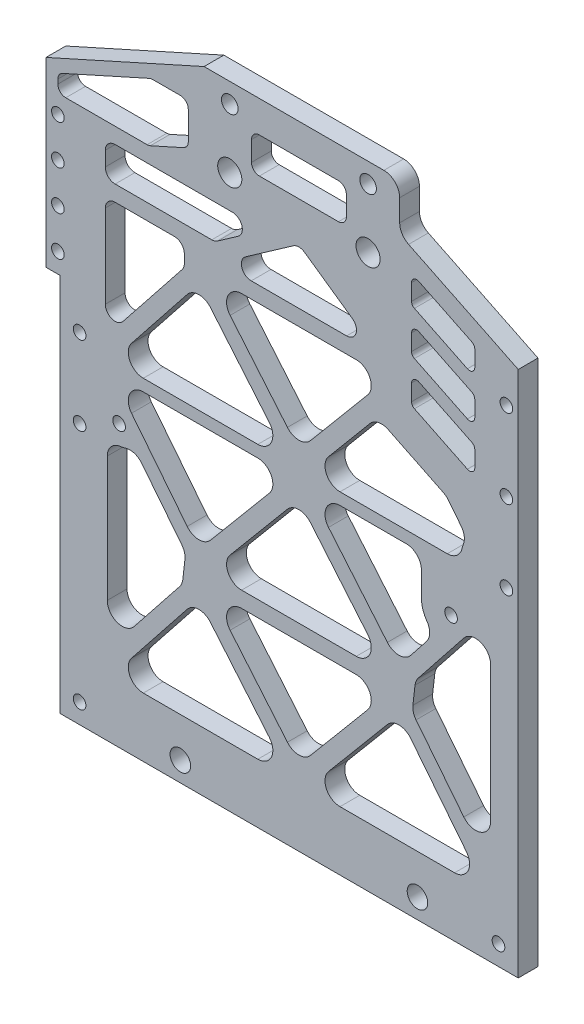
SolidWorks part; units mm, degrees
material "环氧树脂FR-4"
ref_plane "前视基准面" through (0, 0, 0) normal (0, 0, 1) x (1, 0, 0)
ref_plane "上视基准面" through (0, 0, 0) normal (0, 1, 0) x (1, 0, 0)
ref_plane "右视基准面" through (0, 0, 0) normal (1, 0, 0) x (0, 0, -1)
sketch "草图1" plane through (0, 0, 0) normal (0, 0, 1) x (1, 0, 0)
  line L1 (55.5, -80) -> (-55.5, -80)
  line L2 (55.5, -80) -> (55.5, 80)
  line L3 (55.5, 80) -> (-55.5, 80)
  line L4 (-55.5, -80) -> (-55.5, 80)
  line L5 (55.5, -80) -> (-55.5, 80) construction
  line L6 (55.5, 80) -> (-55.5, -80) construction
  point P0 (0, 0)
  dimension "D1" = 111
  dimension "D2" = 160
extrude "凸台-拉伸1" add sketch "草图1" along normal blind 5
sketch "草图2" plane through (0, 0, 5) normal (0, 0, 1) x (1, 0, 0)
  line L0 (0, 80) -> (0, -80) construction
  line L1 (55.5, 80) -> (-55.5, 80) construction
  line L2 (-55.5, -80) -> (55.5, -80) construction
  circle A0 centre (-30, -75) radius 2.6
  circle A1 centre (30, -75) radius 2.6
  dimension "D3" = 5.2
  dimension "D1" = 60
  dimension "D2" = 5
extrude "切除-拉伸1" cut sketch "草图2" against normal through all
sketch "草图6" plane through (0, 0, 5) normal (0, 0, 1) x (1, 0, 0)
  line L0 (0, 80) -> (0, -80) construction
  line L1 (55.5, 80) -> (-55.5, 80) construction
  line L2 (-55.5, -80) -> (55.5, -80) construction
  line L4 (17.5, 60) -> (-17.5, 60) construction
  line L5 (17.5, 60) -> (17.5, 75) construction
  line L6 (17.5, 75) -> (-17.5, 75) construction
  line L7 (-17.5, 60) -> (-17.5, 75) construction
  line L8 (17.5, 60) -> (-17.5, 75) construction
  line L9 (17.5, 75) -> (-17.5, 60) construction
  circle A2 centre (-17.5, 75) radius 2.1
  circle A3 centre (17.5, 75) radius 2.1
  circle A4 centre (17.5, 60) radius 3.0525
  circle A5 centre (-17.5, 60) radius 3.0525
  point P6 (0, 67.5)
  dimension "D4" = 4.2
  dimension "D5" = 6.105
  dimension "D1" = 35
  dimension "D2" = 15
  dimension "D3" = 12.5
extrude "切除-拉伸4" cut sketch "草图6" against normal through all
sketch "草图7" plane through (0, 0, 5) normal (0, 0, 1) x (1, 0, 0)
  line L0 (-17.5, 75) -> (-17.5, 60) construction
  line L2 (17.5, 75) -> (17.5, 60) construction
  line L4 (-17.5, 67.5) -> (17.5, 67.5) construction
  line L6 (10, 63) -> (-10, 63)
  line L7 (12, 65) -> (12, 70)
  line L8 (10, 72) -> (-10, 72)
  line L9 (-12, 65) -> (-12, 70)
  line L10 (12, 63) -> (-12, 72) construction
  line L11 (12, 72) -> (-12, 63) construction
  arc A0 (12, 70) -> (10, 72) centre (10, 70) ccw
  arc A1 (10, 63) -> (12, 65) centre (10, 65) ccw
  arc A2 (-10, 63) -> (-12, 65) centre (-10, 65) cw
  arc A3 (-10, 72) -> (-12, 70) centre (-10, 70) ccw
  point P10 (0, 67.5)
  dimension "D3" = 2
  dimension "D1" = 24
  dimension "D2" = 9
extrude "切除-拉伸5" cut sketch "草图7" against normal through all
sketch "草图8" plane through (0, 0, 5) normal (0, 0, 1) x (1, 0, 0)
  line L5 (25.5, 80) -> (25.5, 68)
  line L8 (55.5, 80) -> (-55.5, 80) construction
  line L9 (25.5, 68) -> (55.5, 53.368)
  line L10 (55.5, -80) -> (55.5, 80) construction
  line L11 (55.5, 53.368) -> (55.5, 80)
  line L12 (55.5, 80) -> (25.5, 80)
  dimension "D1" = 26
  dimension "D2" = 12
  dimension "D3" = 30
extrude "切除-拉伸6" cut sketch "草图8" against normal through all
fillet "圆角1" radius 4 2 edges at (25.5, 80, 2.5) (25.5, 68, 2.5)
sketch "草图10" plane through (0, 0, 0) normal (0, 0, 1) x (1, 0, 0)
  line L0 (-55.5, 80) -> (-64, 80)
  line L1 (-64, 80) -> (-64, 16)
  line L2 (-64, 16) -> (-55.5, 16)
  line L3 (-55.5, 80) -> (-55.5, -80) construction
  line L4 (-55.5, 16) -> (-55.5, 80)
  dimension "D1" = 8.5
  dimension "D2" = 64
extrude "凸台-拉伸3" add sketch "草图10" along normal up to surface (5 mm away) up to face at (12.5699, 33.4098, 5)
sketch "草图11" plane through (0, 0, 5) normal (0, 0, 1) x (1, 0, 0)
  line L0 (-61, 41) -> (-61, 21) construction
  line L1 (-64, 80) -> (-64, 16) construction
  line L2 (-64, 16) -> (-55.5, 16) construction
  line L3 (-61, 51) -> (-61, 41) construction
  circle A0 centre (-61, 21) radius 1.6
  circle A1 centre (-61, 41) radius 1.6
  circle A2 centre (-61, 31) radius 1.6
  circle A3 centre (-61, 51) radius 1.6
  dimension "D3" = 3.2
  dimension "D1" = 20
  dimension "D2" = 3
  dimension "D4" = 5
  dimension "D5" = 10
extrude "切除-拉伸7" cut sketch "草图11" against normal through all
sketch "草图12" plane through (0, 0, 5) normal (0, 0, 1) x (1, 0, 0)
  line L0 (-64, 80) -> (-64, 62)
  line L1 (-64, 80) -> (-64, 16) construction
  line L2 (-64, 62) -> (-24, 80)
  line L3 (21.5, 80) -> (-64, 80) construction
  line L4 (-24, 80) -> (-64, 80)
  dimension "D1" = 18
  dimension "D2" = 40
extrude "切除-拉伸8" cut sketch "草图12" against normal through all
sketch "草图13" plane through (0, 0, 0) normal (0, 0, 1) x (1, 0, 0)
  line L0 (-55.5, -80) -> (-60.5, -80)
  line L1 (-60.5, -80) -> (-60.5, 16)
  line L2 (-64, 16) -> (-55.5, 16) construction
  line L3 (-60.5, 16) -> (-55.5, 16)
  line L4 (-55.5, 16) -> (-55.5, -80) construction
  line L5 (-55.5, 16) -> (-55.5, -80)
  dimension "D1" = 5
extrude "凸台-拉伸4" add sketch "草图13" along normal up to surface (5 mm away) up to face at (-4.6764, 32.8435, 5)
sketch "草图19" plane through (0, 0, 5) normal (0, 0, 1) x (1, 0, 0)
  line L0 (-55.5, -75) -> (50.5, -75) construction
  line L1 (-60.5, 16) -> (-60.5, -80) construction
  line L2 (-60.5, -80) -> (55.5, -80) construction
  line L3 (-55.5, 6) -> (-55.5, -14) construction
  line L4 (-64, 16) -> (-60.5, 16) construction
  line L5 (52.5, 44) -> (52.5, 24) construction
  line L6 (55.5, -80) -> (55.5, 53.368) construction
  line L7 (52.5, 24) -> (52.5, 4) construction
  circle A0 centre (-55.5, -75) radius 1.6
  circle A1 centre (50.5, -75) radius 1.6
  circle A2 centre (-55.5, 6) radius 1.6
  circle A3 centre (-55.5, -14) radius 1.6
  circle A4 centre (52.5, 44) radius 1.6
  circle A5 centre (52.5, 24) radius 1.6
  circle A6 centre (52.5, 4) radius 1.6
  dimension "D1" = 3.2
  dimension "D2" = 5
  dimension "D11" = 20
  dimension "D3" = 5
  dimension "D4" = 20
  dimension "D5" = 5
  dimension "D6" = 10
  dimension "D7" = 5
  dimension "D8" = 20
  dimension "D9" = 3
  dimension "D10" = 44
extrude "切除-拉伸13" cut sketch "草图19" against normal through all
sketch "草图14" plane through (0, 0, 5) normal (0, 0, 1) x (1, 0, 0)
  line L0 (28.5, 60.9738) -> (44.5, 53.1701)
  line L1 (44.5, 53.1701) -> (44.5, 46.1701)
  line L2 (44.5, 46.1701) -> (28.5, 53.9738)
  line L3 (28.5, 53.9738) -> (28.5, 60.9738)
  line L4 (27.7465, 66.9043) -> (55.5, 53.368) construction
  line L5 (55.5, -80) -> (55.5, 53.368) construction
  line L6 (25.5, 76) -> (25.5, 70.4995) construction
  dimension "D1" = 5
  dimension "D2" = 11
  dimension "D3" = 3
  dimension "D4" = 7
extrude "切除-拉伸9" cut sketch "草图14" against normal through all
fillet "圆角2" radius 1.3 4 edges at (44.5, 46.1701, 2.5) (44.5, 53.1701, 2.5) (28.5, 53.9738, 2.5) (28.5, 60.9738, 2.5)
pattern_linear "阵列(线性)1" count 3 spacing 11 along (0, -1, 0) of "切除-拉伸9", "圆角2"
sketch "草图17" plane through (0, 0, 5) normal (0, 0, 1) x (1, 0, 0)
  line L0 (-61, 60.0602) -> (-37.4444, 70.6602)
  line L1 (-28, 70.6602) -> (-28, 55.6602)
  line L3 (-64, 62) -> (-24, 80) construction
  line L4 (-61, 60.0602) -> (-61, 55.6602)
  line L5 (-61, 55.6602) -> (-28, 55.6602)
  line L6 (-64, 62) -> (-64, 16) construction
  line L7 (-37.4444, 70.6602) -> (-28, 70.6602)
  dimension "D1" = 3
  dimension "D2" = 3
  dimension "D3" = 4.4
  dimension "D4" = 33
  dimension "D5" = 15
extrude "切除-拉伸11" cut sketch "草图17" against normal through all
chamfer "倒角2" distance 10 angle 24.23 1 edges at (-28, 55.6602, 2.5)
fillet "圆角3" radius 2 6 edges at (-61, 60.0602, 2.5) (-28, 70.6602, 2.5) (-37.4444, 70.6602, 2.5) (-61, 55.6602, 2.5) (-38, 55.6602, 2.5) (-28, 60.1607, 2.5)
sketch "草图21" plane through (0, 0, 5) normal (0, 0, 1) x (1, 0, 0)
  line L0 (38.5, -9) -> (-45.5, -9) construction
  line L1 (-60.5, -80) -> (55.5, -80) construction
  circle A0 centre (-45.5, -9) radius 1.6
  circle A1 centre (38.5, -9) radius 1.6
  dimension "D1" = 84
  dimension "D2" = 71
  dimension "D3" = 3.2
  dimension "D4" = 38.5
extrude "切除-拉伸14" cut sketch "草图21" against normal through all
sketch "草图20" plane through (0, 0, 0) normal (0, 0, -1) x (-1, 0, 0)
  line L6 (0, 0) -> (0, -80) construction
  line L7 (60.5, -80) -> (-55.5, -80) construction
  line L14 (22.6557, -34) -> (-22.6557, -34)
  line L22 (-22.6557, -34) -> (0, -61)
  line L23 (-2.25, -65) -> (-25.3804, -37.4343)
  line L24 (-25.3804, -37.4343) -> (-47.25, -65)
  line L25 (-47.25, -65) -> (-2.25, -65)
  line L29 (60.5, -80) -> (-55.5, -80) construction
  line L30 (0, 2.5) -> (60.5, 2.5) construction
  line L38 (47.25, -65) -> (2.25, -65)
  line L39 (25.3804, -37.4343) -> (47.25, -65)
  line L40 (2.25, -65) -> (25.3804, -37.4343)
  line L41 (22.6557, -34) -> (0, -61)
  line L43 (0, -32) -> (60.5, -32) construction
  line L44 (60.5, 16) -> (60.5, -80) construction
  line L45 (22.6557, -30) -> (-22.6557, -30)
  line L46 (-22.6557, -34) -> (0, -61)
  line L47 (-2.25, -65) -> (-25.3804, -37.4343)
  line L48 (-25.3804, -37.4343) -> (-47.25, -65)
  line L49 (-47.25, -65) -> (-2.25, -65)
  line L53 (-25.3804, -26.5657) -> (-47.25, 1)
  line L54 (47.25, -65) -> (2.25, -65)
  line L55 (25.3804, -37.4343) -> (47.25, -65)
  line L56 (2.25, -65) -> (25.3804, -37.4343)
  line L57 (22.6557, -34) -> (0, -61)
  line L58 (-47.25, 1) -> (-2.25, 1)
  line L59 (-2.25, 1) -> (-25.3804, -26.5657)
  line L60 (-22.6557, -30) -> (0, -3)
  line L61 (47.25, 1) -> (2.25, 1)
  line L62 (25.3804, -26.5657) -> (47.25, 1)
  line L63 (2.25, 1) -> (25.3804, -26.5657)
  line L64 (22.6557, -30) -> (0, -3)
  line L65 (-48.5, -60.1397) -> (-26.1749, -32)
  line L66 (-31, 1) -> (-31, -9)
  line L67 (31, 1) -> (31, -9)
  line L68 (25.3804, 31.5657) -> (47.25, 4)
  line L69 (2.25, 4) -> (25.3804, 31.5657)
  line L71 (-48.5, -3.8603) -> (-48.5, -60.1397)
  line L72 (-55.5, -80) -> (-55.5, 53.368) construction
  line L73 (48.5, -60.1397) -> (26.1749, -32)
  line L74 (48.5, -3.8603) -> (48.5, -60.1397)
  line L75 (48.5, -3.8603) -> (26.1749, -32)
  line L76 (-48.5, -3.8603) -> (-26.1749, -32)
  line L77 (47.25, 4) -> (2.25, 4)
  line L78 (22.6557, 35) -> (0, 8)
  line L79 (-22.6557, 35) -> (0, 8)
  line L80 (22.6557, 35) -> (-22.6557, 35)
  line L81 (-2.25, 4) -> (-25.3804, 31.5657)
  line L82 (-47.25, 4) -> (-2.25, 4)
  line L83 (-25.3804, 31.5657) -> (-47.25, 4)
  line L84 (-19.9047, 25.04) -> (-37.2816, 16.5647)
  line L85 (-29.2301, 31.6177) -> (-42.6301, 25.0821) construction
  line L86 (-48.5, -16.5) -> (-38.5, -16.5)
  line L87 (-38.5, -1.5) -> (-38.5, 1)
  circle A2 centre (-38.5, -9) radius 7.5
  circle A5 centre (-52.5, 4) radius 11.6321
  circle A6 centre (45.5, -9) radius 4.8443
  point P17 (-43.6454, -3.5434)
  point P31 (0, -34)
  point P59 (48.5, -32)
  point P60 (-48.5, -32)
  dimension "D7" = 15
  dimension "D3" = 3
  dimension "D1" = 15
  dimension "D2" = 4.5
  dimension "D4" = 27
  dimension "D5" = 40
  dimension "D6" = 45
  dimension "D8" = 4
  dimension "D9" = 7
  dimension "D10" = 10
  dimension "D11" = 19
  dimension "D12" = 2
extrude "切除-拉伸22" cut sketch "草图20" against normal through all
chamfer "倒角1" distance 4 angle 45 2 edges at (-26.1749, -32, 2.5) (26.1749, -32, 2.5)
fillet "圆角5" radius 3.8 39 edges at (22.6557, -34, 2.5) (-22.6557, -34, 2.5) (0, -61, 2.5) (-47.25, -65, 2.5) (-2.25, -65, 2.5) (-25.3804, -37.4343, 2.5) (2.25, 1, 2.5) (25.3804, -26.5657, 2.5) (34.3566, -15.2516, 2.5) (0, -3, 2.5) (-22.6557, -30, 2.5) (-29.5058, -36.1984, 2.5) (-28.661, -28.8664, 2.5) (-48.5, -60.1397, 2.5) (29.5058, -27.8016, 2.5) (28.661, -35.1336, 2.5) (48.5, -60.1397, 2.5) (25.3804, -37.4343, 2.5) (2.25, -65, 2.5) (47.25, -65, 2.5) (-25.3804, -26.5657, 2.5) (-2.25, 1, 2.5) (-47.25, 1, 2.5) (22.6557, -30, 2.5) (31, 1, 2.5) (22.6557, 35, 2.5) (-22.6557, 35, 2.5) (0, 8, 2.5) (2.25, 4, 2.5) (40.8679, 4, 2.5) (42.5154, 9.9677, 2.5) (-25.3804, 31.5657, 2.5) (-47.25, 4, 2.5) (-2.25, 4, 2.5) (19.9047, 25.04, 2.5) (37.2816, 16.5647, 2.5) (-48.5, -12.8035, 2.5) (-41.8739, -12.2122, 2.5) (48.5, -3.8603, 2.5)
sketch "草图23" plane through (0, 0, 0) normal (0, 0, -1) x (-1, 0, 0)
  line L0 (-22.5, 8) -> (-44.5, 8)
  line L1 (-44.5, 8) -> (-44.5, 18)
  line L2 (-44.5, 18) -> (-30.6678, 24.7464)
  line L4 (0.2882, 8) -> (-12.2588, 33.7251)
  line L5 (-12.2588, 33.7251) -> (3.8979, 41.6052)
  line L6 (3.8979, 41.6052) -> (20.2882, 8)
  line L7 (20.2882, 8) -> (0.2882, 8)
  line L8 (25.8512, 8) -> (8.3918, 43.7971)
  line L10 (45.8512, 32.8401) -> (45.8512, 8)
  line L11 (45.8512, 8) -> (25.8512, 8)
  line L12 (-27.2, 1) -> (-10.3991, 1) construction
  line L13 (-29.2301, 31.6177) -> (-42.6301, 25.0821) construction
  line L14 (-44.5, 26.2505) -> (-44.5, 30.3577) construction
  line L15 (-19.1622, 8) -> (-27.9714, 26.0615)
  line L16 (-27.9714, 26.0615) -> (-15.8539, 31.9716)
  line L17 (-15.8539, 31.9716) -> (-4.1622, 8)
  line L18 (-4.1622, 8) -> (-19.1622, 8)
  line L20 (8.3918, 43.7971) -> (14.6834, 46.8657)
  line L21 (-37.629, 8) -> (28.9212, 40.4587)
  line L22 (-30.7855, 8) -> (32.4806, 38.8569)
  line L23 (20.2882, 8) -> (45.8512, 20.4679)
  line L24 (13.4447, 8) -> (45.8512, 23.8057)
  line L25 (-30.6678, 24.7464) -> (-22.5, 8)
  line L26 (14.6834, 46.8657) -> (45.8512, 32.8401)
  line L27 (37.8359, 70.4841) -> (59.8207, 60.5909) construction
  dimension "D1" = 7
  dimension "D2" = 22
  dimension "D3" = 10
  dimension "D4" = 3
  dimension "D5" = 4
  dimension "D6" = 15
  dimension "D7" = 20
  dimension "D8" = 5
  dimension "D9" = 20
  dimension "D10" = 12
  dimension "D11" = 3
  dimension "D12" = 3
  dimension "D13" = 7
extrude "切除-拉伸23" [suppressed] cut sketch "草图23" against normal through all contours L25 L2 L1 L0 L21 | L15 L21 L17 L16 | L22 L15 L18 L17 | L7 L24 L6 L22 L4 | L4 L21 L6 L5 | L26 L20 L8 L21 | L26 L22 L8 L24 L10 | L23 L8 L11 L10
sketch "草图24" plane through (0, 0, 0) normal (0, 0, -1) x (-1, 0, 0)
  line L1 (49, 39) -> (49, 8.23)
  line L2 (49, 8.23) -> (29, 33.4391)
  line L3 (29, 33.4391) -> (29, 39)
  line L4 (-20, 39) -> (0, 53)
  line L7 (0, 53) -> (20, 39)
  line L8 (20, 39) -> (-20, 39)
  line L9 (0, 53) -> (0, 0) construction
  line L10 (14.5066, 35) -> (-14.5066, 35) construction
  line L12 (28.2748, 27.9174) -> (42.3615, 10.1618) construction
  line L14 (64, 62) -> (64, 16) construction
  line L15 (49, 39) -> (29, 39)
  line L16 (8.8891, 51.6602) -> (21.2609, 43)
  line L17 (21.2609, 43) -> (49, 43)
  line L18 (49, 43) -> (49, 51.6602)
  line L19 (49, 51.6602) -> (8.8891, 51.6602)
  line L20 (59, 55.6602) -> (38.4293, 55.6602) construction
  point P12 (0, 39)
  dimension "D1" = 4
  dimension "D2" = 14
  dimension "D3" = 40
  dimension "D4" = 4
  dimension "D5" = 4
  dimension "D6" = 15
  dimension "D7" = 20
  dimension "D8" = 4
  dimension "D9" = 4
extrude "切除-拉伸24" cut sketch "草图24" against normal through all
fillet "圆角6" radius 2.5 11 edges at (-49, 39, 2.5) (-49, 8.23, 2.5) (-29, 33.4391, 2.5) (-29, 39, 2.5) (-49, 51.6602, 2.5) (-49, 43, 2.5) (-21.2609, 43, 2.5) (-8.8891, 51.6602, 2.5) (0, 53, 2.5) (20, 39, 2.5) (-20, 39, 2.5)
